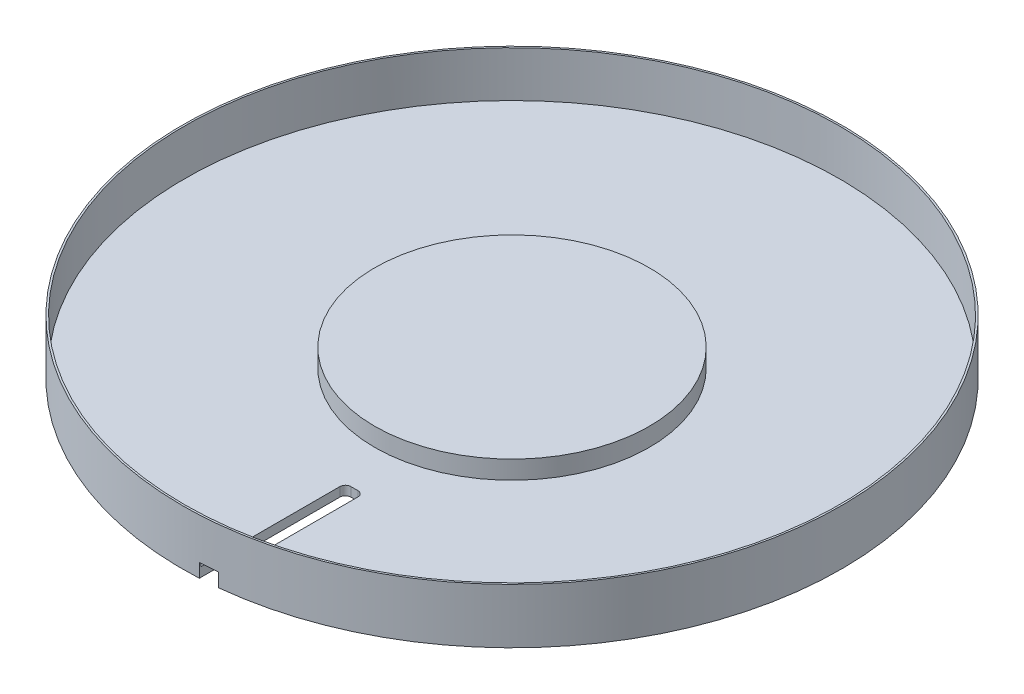
SolidWorks part; units mm, degrees
ref_plane "Płaszczyzna przednia" through (0, 0, 0) normal (0, 0, 1) x (1, 0, 0)
ref_plane "Płaszczyzna górna" through (0, 0, 0) normal (0, 1, 0) x (1, 0, 0)
ref_plane "Płaszczyzna prawa" through (0, 0, 0) normal (1, 0, 0) x (0, 0, -1)
sketch "Sketch1" plane through (0, 0, 0) normal (0, 1, 0) x (1, 0, 0)
  line L0 (0, 0) -> (0, -360) construction
  circle A0 centre (0, 0) radius 360
  dimension "D1" = 720
extrude "Boss-Extrude1" add sketch "Sketch1" along normal blind 60
sketch "Sketch2" plane through (0, 60, 0) normal (0, 1, 0) x (1, 0, 0)
  circle A0 centre (0, 0) radius 358
  circle A1 centre (0, 0) radius 150
  circle A2 centre (0, 0) radius 360 construction
  dimension "D1" = 2
  dimension "D2" = 300
extrude "Cut-Extrude1" cut sketch "Sketch2" against normal offset from surface (50 mm away) 10 up to face at (0, 0, 360)
ref_plane "Plane1" through (0, 0, 360) normal (0, 0, 1) x (1, 0, 0)
sketch "Sketch3" plane through (0, 0, 360) normal (0, 0, 1) x (1, 0, 0)
  line L0 (20, 12) -> (20, -309) construction
  line L1 (18, 0) -> (37.6735, 0)
  line L2 (18, 0) -> (18, 15)
  line L3 (18, 15) -> (37.6735, 15)
  line L4 (37.6735, 0) -> (37.6735, 15)
  line L5 (33.6735, 12) -> (33.6735, -309) construction
  line L6 (360, 0) -> (-360, 0) construction
  dimension "D1" = 2
  dimension "D2" = 4
  dimension "D3" = 15
extrude "Cut-Extrude2" cut sketch "Sketch3" against normal blind 160
other "Move Face1" face at (0, 60, 150) parameters "D1"=30
fillet "Fillet1" radius 6 2 edges at (37.6735, 5, 200) (18, 5, 200)
